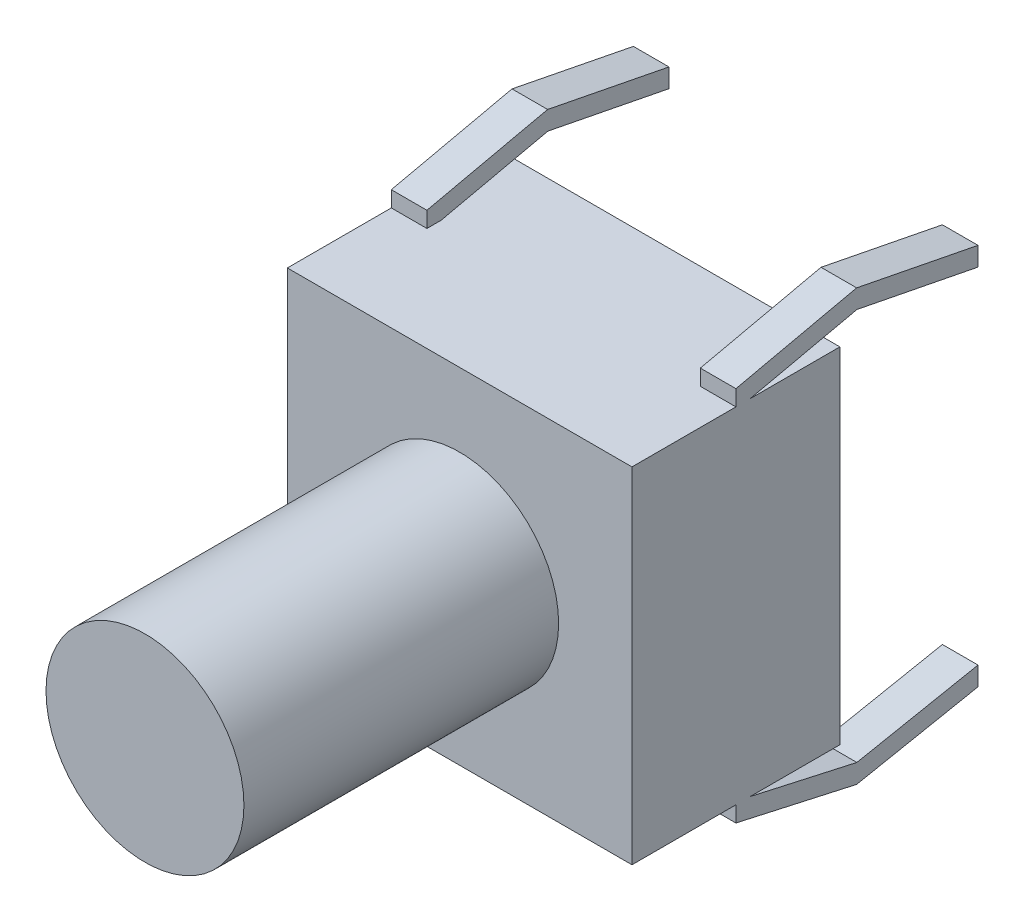
SolidWorks part; units mm, degrees
ref_plane "Front Plane" through (0, 0, 0) normal (0, 0, 1) x (1, 0, 0)
ref_plane "Top Plane" through (0, 0, 0) normal (0, 1, 0) x (1, 0, 0)
ref_plane "Right Plane" through (0, 0, 0) normal (1, 0, 0) x (0, 0, -1)
sketch "Sketch1" plane through (0, 0, 0) normal (0, 0, 1) x (1, 0, 0)
  line L1 (-3.0734, -3.0734) -> (3.0734, -3.0734)
  line L2 (-3.0734, -3.0734) -> (-3.0734, 3.0734)
  line L3 (-3.0734, 3.0734) -> (3.0734, 3.0734)
  line L4 (3.0734, -3.0734) -> (3.0734, 3.0734)
  line L5 (-3.0734, -3.0734) -> (3.0734, 3.0734) construction
  line L6 (-3.0734, 3.0734) -> (3.0734, -3.0734) construction
  point P0 (0, 0)
  dimension "D1" = 6.1468
  dimension "D2" = 6.1468
extrude "Boss-Extrude1" add sketch "Sketch1" along normal blind 3.7084
sketch "Sketch2" plane through (0, 0, 3.7084) normal (0, 0, 1) x (1, 0, 0)
  circle A0 centre (0, 0) radius 1.7653
  dimension "D1" = 3.5306
extrude "Boss-Extrude2" add sketch "Sketch2" along normal blind 5.6134 contours A0
sketch "Sketch3" plane through (-3.0734, 0, 0) normal (-1, 0, 0) x (0, 0, 1)
  line L0 (1.8542, 3.0734) -> (1.8542, 3.3551)
  line L1 (3.7084, 3.0734) -> (0, 3.0734) construction
  line L2 (1.8542, 3.3551) -> (-0.299, 3.8354)
  line L3 (-0.299, 3.8354) -> (-2.4638, 3.4099)
  line L4 (-2.4638, 3.4099) -> (-2.4638, 3.0734)
  line L5 (-2.4638, 3.0734) -> (-0.3033, 3.498)
  line L6 (-0.3033, 3.498) -> (1.6002, 3.0734)
  line L7 (1.6002, 3.0734) -> (1.8542, 3.0734)
  point P4 (1.3559, 3.7405)
  point P10 (1.0332, 5.8666)
  point P11 (-1.2388, 3.6751)
  point P12 (-0.9271, 3.0734)
  point P13 (-0.1933, 4.5999)
  point P14 (-0.1839, 4.8183)
  point P15 (-1.4235, 3.9111)
  point P16 (1.3743, 4.0496)
  point P17 (-3.0025, 3.1632)
  point P18 (0.3632, 4.0704)
  point P19 (1.8542, 3.3145)
  point P20 (1.5664, 3.0734)
  point P21 (-0.0898, 3.4305)
  point P22 (-0.6162, 3.4178)
  point P23 (-2.9478, 3.0203)
  point P24 (0, 0)
  point P26 (-0.8829, 3.4079)
  point P27 (-0.5697, 3.3752)
  dimension "D1" = 0.3302
  dimension "D2" = 0.3302
  dimension "D3" = 4.318
  dimension "D4" = 0.762
  dimension "D5" = 0.254
extrude "Boss-Extrude3" add sketch "Sketch3" against normal blind 0.635
ref_plane "Plane1" through (0, 0, 0) normal (-1, 0, 0) x (0, 0, 1)
mirror "Mirror1" about plane through (0, 0, 0) normal (-1, 0, 0) of "Boss-Extrude3"
ref_plane "Plane2" through (0, 0, 0) normal (0, 1, 0) x (1, 0, 0)
mirror "Mirror2" about plane through (0, 0, 0) normal (0, 1, 0) of "Mirror1", "Boss-Extrude3"
